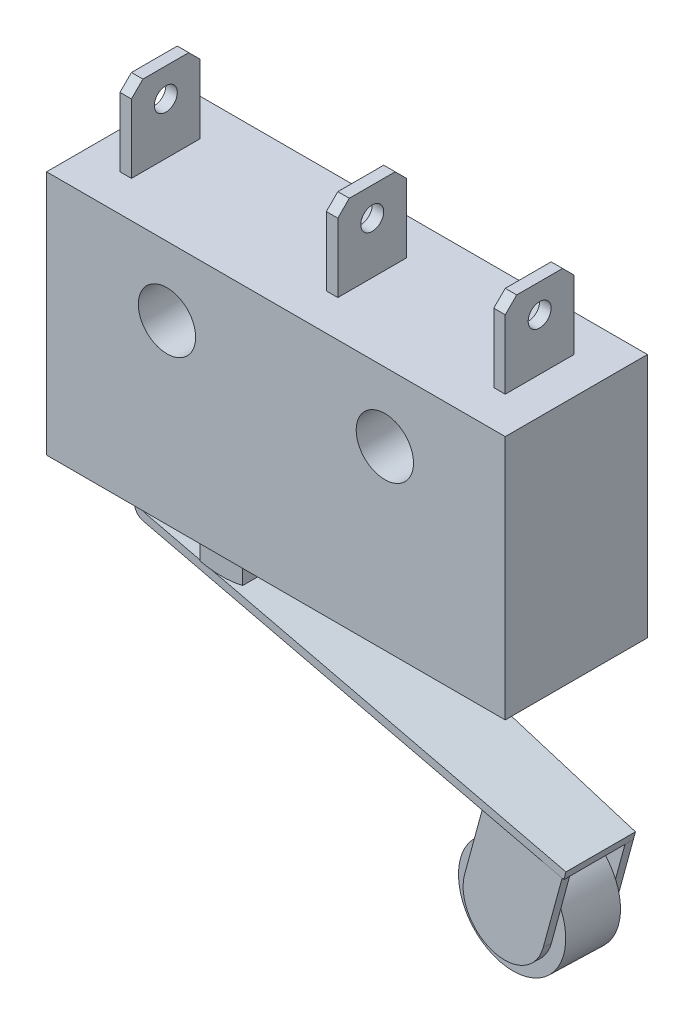
SolidWorks part; units mm, degrees
other "Markup1"
sketch "Sketch6" plane through (0, -5.3382, -3.1) normal (0, -1, 0) x (1, 0, 0)
material "PVC 0.007 Plasticized"
ref_plane "Front Plane" through (0, 0, 0) normal (0, 0, 1) x (1, 0, 0)
ref_plane "Top Plane" through (0, 0, 0) normal (0, 1, 0) x (1, 0, 0)
ref_plane "Right Plane" through (0, 0, 0) normal (1, 0, 0) x (0, 0, -1)
sketch "Sketch1" plane through (0, 0, 0) normal (0, 0, 1) x (1, 0, 0)
  line L1 (0, 0) -> (20, 0)
  line L2 (0, 0) -> (0, 10.7)
  line L3 (0, 10.7) -> (20, 10.7)
  line L4 (20, 0) -> (20, 10.7)
  dimension "D1" = 20
  dimension "D2" = 10.7
extrude "Boss-Extrude1" add sketch "Sketch1" along normal mid plane 6.2
sketch "Sketch2" plane through (0, 0, 0) normal (0, 0, 1) x (1, 0, 0)
  line L0 (20, 10.7) -> (0, 10.7) construction
  line L1 (2.1, 10.7) -> (1.6, 10.7)
  line L2 (2.1, 10.7) -> (2.1, 14.2)
  line L3 (2.1, 14.2) -> (1.6, 14.2)
  line L4 (1.6, 10.7) -> (1.6, 14.2)
  line L5 (1.85, 14.2) -> (18.15, 14.2) construction
  line L6 (18.4, 10.7) -> (17.9, 10.7)
  line L7 (18.4, 10.7) -> (18.4, 14.2)
  line L8 (18.4, 14.2) -> (17.9, 14.2)
  line L9 (17.9, 10.7) -> (17.9, 14.2)
  line L10 (11.1, 10.7) -> (10.6, 10.7)
  line L11 (11.1, 10.7) -> (11.1, 14.2)
  line L12 (11.1, 14.2) -> (10.6, 14.2)
  line L13 (10.6, 10.7) -> (10.6, 14.2)
  point P14 (1.85, 14.2)
  point P15 (18.15, 14.2)
  point P16 (10.85, 14.2)
  point P20 (10, 10.7)
  point P21 (10, 14.2)
  dimension "D1" = 16.3
  dimension "D2" = 0.5
  dimension "D3" = 7.3
  dimension "D4" = 3.5
extrude "Boss-Extrude2" add sketch "Sketch2" along normal mid plane 3
chamfer "Chamfer1" distance 0.5 angle 45 6 edges at (1.85, 14.2, -1.5) (1.85, 14.2, 1.5) (10.85, 14.2, -1.5) (10.85, 14.2, 1.5) (18.15, 14.2, 1.5) (18.15, 14.2, -1.5)
sketch "Sketch3" plane through (18.4, 0, 0) normal (1, 0, 0) x (0, 0, -1)
  line L0 (-1, 14.2) -> (1, 14.2) construction
  circle A0 centre (0, 12.95) radius 0.5
  point P5 (0, 14.2)
  dimension "D1" = 1.25
  dimension "D2" = 1
extrude "Cut-Extrude1" cut sketch "Sketch3" against normal up to surface (16.8 mm away) up to face at (1.6, 12.8667, 0)
sketch "Sketch4" plane through (0, 0, -3.1) normal (0, 0, -1) x (-1, 0, 0)
  line L0 (-20, 10.7) -> (0, 10.7) construction
  line L1 (-5.25, 7.7) -> (-14.75, 7.7) construction
  circle A0 centre (-5.25, 7.7) radius 1.25
  circle A1 centre (-14.75, 7.7) radius 1.25
  point P4 (-10, 10.7)
  point P5 (-10, 7.7)
  dimension "D1" = 9.5
  dimension "D3" = 2.5
  dimension "D2" = 3
extrude "Cut-Extrude2" cut sketch "Sketch4" against normal through all
sketch "Sketch5" plane through (0, 0, 0) normal (0, 0, 1) x (1, 0, 0)
  line L4 (2.75, 0) -> (2.75, -1)
  line L5 (0, 0) -> (20, 0) construction
  line L6 (3.2106, -1.1447) -> (21.0621, -6)
  line L8 (3.1, -1) -> (3.1, 0)
  line L9 (21.0621, -6) -> (20.9703, -6.3377)
  line L10 (3.1188, -1.4825) -> (20.9703, -6.3377)
  line L11 (0, 10.7) -> (0, 0) construction
  line L12 (2.75, 0) -> (3.1, 0)
  line L13 (5.6, 0) -> (7.45, 0)
  line L14 (5.6, 0) -> (5.6, -1.75)
  line L15 (7.45, 0) -> (7.45, -1.75)
  arc A0 (2.75, -1) -> (3.1188, -1.4825) centre (3.25, -1) ccw
  arc A1 (3.1, -1) -> (3.2106, -1.1447) centre (3.25, -1) ccw
  arc A2 (5.6, -1.75) -> (7.45, -1.75) centre (6.525, 2.1416) ccw
  dimension "D1" = 0.35
  dimension "D6" = 0.5
  dimension "D9" = 1.85
  dimension "D8" = 4
  dimension "D2" = 1
  dimension "D3" = 2.75
  dimension "D4" = 18.5
  dimension "D5" = 6
  dimension "D7" = 2.5
  dimension "D10" = 1.75
extrude "Boss-Extrude3" add sketch "Sketch5" along normal mid plane 4
ref_plane "Plane1" through (3.2794, -0.8919, 0) normal (0.9649, -0.2624, 0) x (0, 0, -1)
draft "Draft10" type of draft neutral plane draft angle 1.5 neutral plane "Plane1" faces to draft 2 face at (7.4945, -2.1308, -2) face at (7.4945, -2.1308, 2) neutral plane through (3.2794, -0.8919, 0) neutral plane normal (0.9649, -0.2624, 0) parameters "D1"=1.5
sketch "Sketch7" plane through (0.0527, -0.0143, -2.0876) normal (0.0253, -0.0069, -0.9997) x (-0.9997, -0.0002, -0.0253)
  line L0 (-17.4941, -5.0311) -> (-21.0161, -5.9894)
  line L1 (-17.4941, -5.0311) -> (-16.5753, -8.4084)
  line L2 (-21.0161, -5.9894) -> (-20.0973, -9.3666)
  line L5 (-21.0161, -5.9894) -> (-3.1589, -1.131) construction
  line L6 (-3.067, -1.4687) -> (-20.9242, -6.3271) construction
  line L8 (-20.9242, -6.3271) -> (-21.0161, -5.9894) construction
  arc A0 (-16.5753, -8.4084) -> (-20.0973, -9.3666) centre (-18.3363, -8.8875) cw
  dimension "D1" = 3.65
  dimension "D2" = 3.5
extrude "Boss-Extrude4" add sketch "Sketch7" against normal blind 0.35
ref_plane "Plane3" through (0.0145, -0.0039, -0.573) normal (0.0253, -0.0069, -0.9997) x (-0.9997, -0.0002, -0.0253)
mirror "Mirror1" about plane through (0.0145, -0.0039, -0.573) normal (0.0253, -0.0069, -0.9997) of "Boss-Extrude4"
sketch "Sketch8" plane through (-0.0149, 0.0041, 0.5916) normal (0.0253, -0.0069, -0.9997) x (-0.9997, -0.0002, -0.0253)
  circle A0 centre (-18.3363, -8.8876) radius 2.4
  arc A1 (-20.0972, -9.3667) -> (-16.5753, -8.4084) centre (-18.3363, -8.8876) ccw construction
  dimension "D1" = 4.8
extrude "Boss-Extrude5" add sketch "Sketch8" along normal up to surface (2.3301 mm away) up to face at (18.6679, -7.8166, -1.2135)
